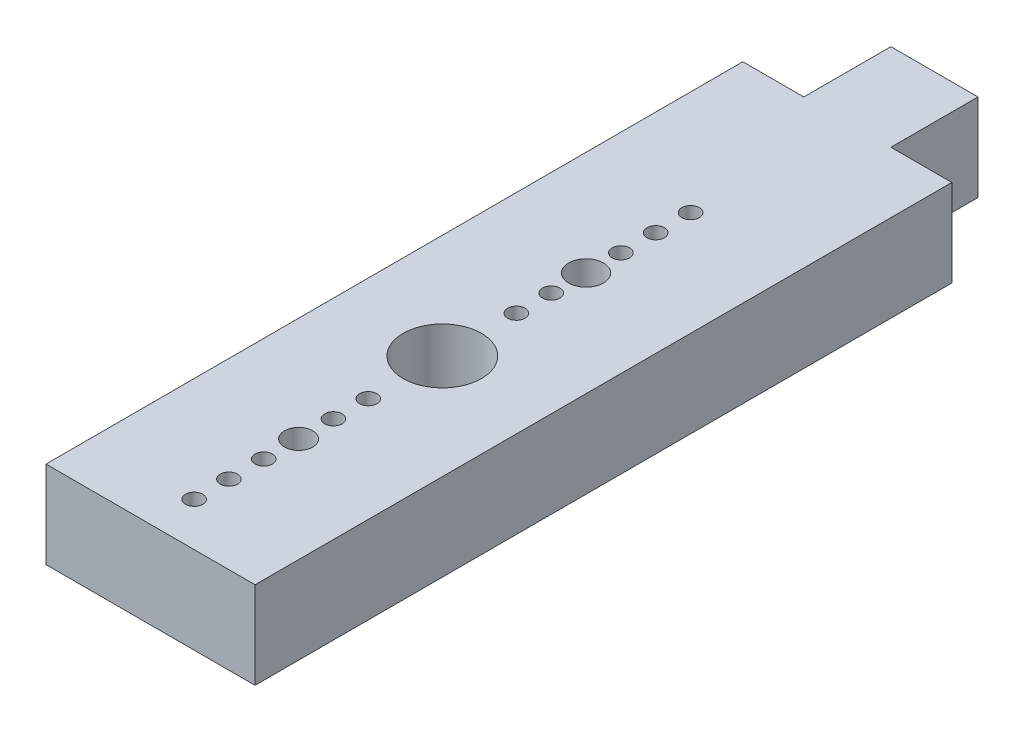
SolidWorks part; units mm, degrees
material "Acrylic (Medium-high impact)"
ref_plane "Front Plane" through (0, 0, 0) normal (0, 0, 1) x (1, 0, 0)
ref_plane "Top Plane" through (0, 0, 0) normal (0, 1, 0) x (1, 0, 0)
ref_plane "Right Plane" through (0, 0, 0) normal (1, 0, 0) x (0, 0, -1)
sketch "Sketch1" plane through (0, 0, 0) normal (0, 1, 0) x (1, 0, 0)
  line L0 (-2.5, 20) -> (-2.5, 25)
  line L1 (-6, 20) -> (-2.5, 20)
  line L2 (-6, 20) -> (-6, -20)
  line L3 (-6, -20) -> (6, -20)
  line L4 (6, 20) -> (6, -20)
  line L7 (-2.5, 25) -> (2.5, 25)
  line L8 (2.5, 25) -> (2.5, 20)
  line L9 (2.5, 20) -> (6, 20)
  circle A0 centre (0, 11) radius 0.5
  circle A1 centre (0, 9) radius 0.5
  circle A2 centre (0, 7) radius 0.5
  circle A4 centre (0, 3) radius 0.5
  circle A5 centre (0, 1) radius 0.5
  circle A6 centre (0, -7.5) radius 0.5
  circle A7 centre (0, -9.5) radius 0.5
  circle A9 centre (0, -13.5) radius 0.5
  circle A10 centre (0, -15.5) radius 0.5
  circle A11 centre (0, -17.5) radius 0.5
  circle A12 centre (0, -3.25) radius 2.25
  circle A13 centre (0, 5) radius 0.5 [skipped]
  circle A14 centre (0, -11.5) radius 0.5 [skipped]
  circle A15 centre (0, 5) radius 1
  circle A16 centre (0, -11.5) radius 0.8112
  point P0 (0, 0)
  point P8 (0, 25)
  point P11 (0, -20)
  point P13 (-6, 0)
  point P39 (0, 0)
  point P44 (0, 0)
  dimension "D5" = 1
  dimension "D8" = 2
  dimension "D9" = 1
  dimension "D13" = 4.5
  dimension "D15" = 2
  dimension "D1" = 12
  dimension "D2" = 40
  dimension "D3" = 5
  dimension "D4" = 5
  dimension "D6" = 9
  dimension "D10" = 8.5
  dimension "D12" = 2
  dimension "D14" = 4.25
  dimension "D16" = 2
  dimension "D17" = 2
  dimension "D7" = 6
  dimension "D11" = 6
extrude "Boss-Extrude1" add sketch "Sketch1" along normal blind 5
